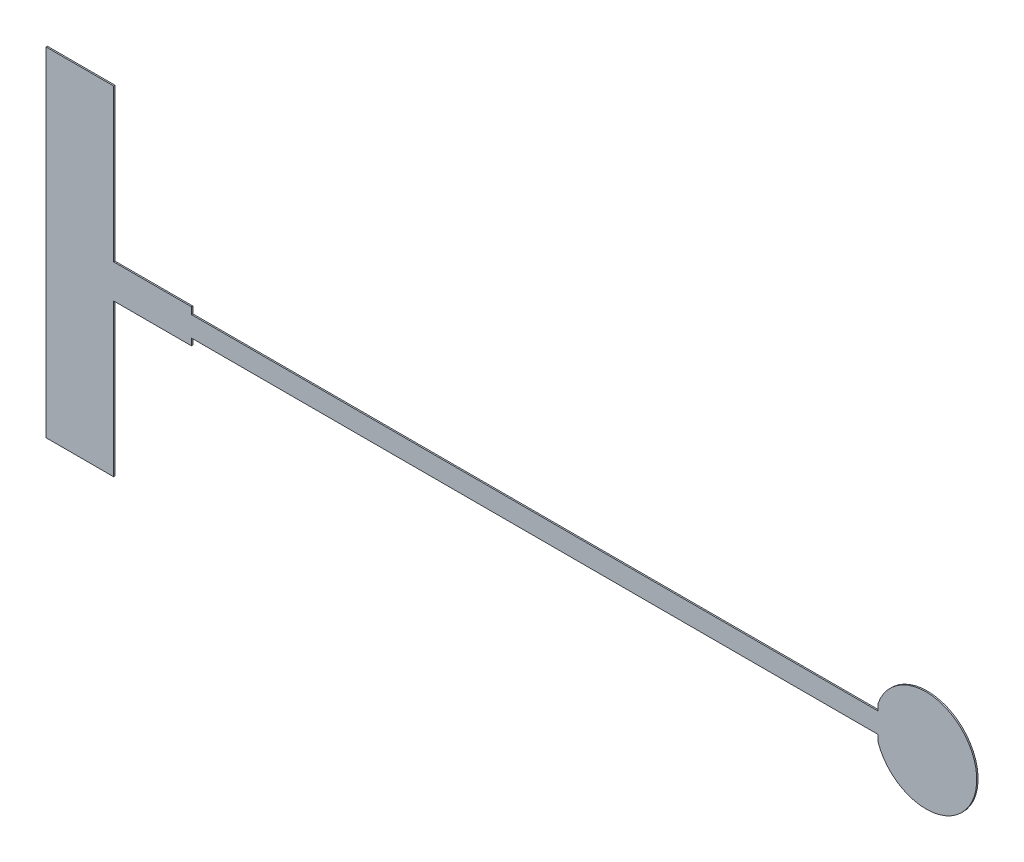
SolidWorks part; units mm, degrees
ref_plane "Front Plane" through (0, 0, 0) normal (0, 0, 1) x (1, 0, 0)
ref_plane "Top Plane" through (0, 0, 0) normal (0, 1, 0) x (1, 0, 0)
ref_plane "Right Plane" through (0, 0, 0) normal (1, 0, 0) x (0, 0, -1)
sketch "Sketch1" plane through (0, 0, 0) normal (0, 0, 1) x (1, 0, 0)
  line L0 (1000, 250) -> (5000, 250)
  line L1 (-1000, 2500) -> (1000, 2500)
  line L2 (-1000, 2500) -> (-1000, -2500)
  line L3 (-1000, -2500) -> (1000, -2500)
  line L4 (1000, 2500) -> (1000, 250)
  line L5 (-1000, 2500) -> (1000, -2500) construction
  line L6 (-1000, -2500) -> (1000, 2500) construction
  line L9 (1000, -250) -> (5000, -250)
  line L10 (5000, 250) -> (5000, 125)
  line L11 (-3000, 250) -> (5000, -250) construction
  line L12 (-3000, -250) -> (5000, 250) construction
  line L13 (5000, 125) -> (9000, 125)
  line L15 (5000, -125) -> (9000, -125)
  line L16 (9000, 125) -> (9000, 100)
  line L17 (1000, 125) -> (9000, -125) construction
  line L18 (1000, -125) -> (9000, 125) construction
  line L19 (9000, 100) -> (11256.6966, 100)
  line L21 (9000, -100) -> (11256.6966, -100)
  line L23 (6000, 100) -> (12000, -100) construction
  line L24 (6000, -100) -> (12000, 100) construction
  line L25 (1000, -250) -> (1000, -2500)
  line L26 (5000, -125) -> (5000, -250)
  line L27 (9000, -100) -> (9000, -125)
  arc A0 (11256.6966, -100) -> (11256.6966, 100) centre (12000, 0) ccw
  point P0 (0, 0)
  point P6 (1000, 0)
  point P11 (5000, 0)
  point P16 (9000, 0)
  dimension "D9" = 1500
  dimension "D1" = 2000
  dimension "D2" = 5000
  dimension "D3" = 500
  dimension "D4" = 4000
  dimension "D5" = 250
  dimension "D6" = 4000
  dimension "D7" = 200
extrude "Boss-Extrude1" add sketch "Sketch1" against normal blind 20
sketch "Sketch2" plane through (0, 0, 0) normal (0, 0, 1) x (1, 0, 0)
  line L0 (0, -11) -> (0, 11) construction
  line L1 (1000, 2500) -> (0, 2500)
  line L2 (1000, 2500) -> (1000, 250)
  line L3 (1000, 250) -> (0, 250)
  line L4 (0, 2500) -> (0, 250)
  line L5 (1000, -2500) -> (0, -2500)
  line L6 (1000, -2500) -> (1000, -250)
  line L7 (1000, -250) -> (0, -250)
  line L8 (0, -2500) -> (0, -250)
  dimension "D1" = 1000
  dimension "D2" = 2250
extrude "Cut-Extrude1" cut sketch "Sketch2" against normal through all
sketch "Sketch3" plane through (0, 0, 0) normal (0, 0, 1) x (1, 0, 0)
  line L0 (0, 0) -> (1098.3807, 0) construction
  line L1 (11, 0) -> (-11, 0) construction
  line L2 (5000, 250) -> (0, 250) construction
  line L3 (1500, 250) -> (3250, 250)
  line L4 (1500, 250) -> (1500, 200)
  line L5 (1500, 200) -> (3250, 200)
  line L7 (0, -250) -> (5000, -250) construction
  line L8 (1500, -250) -> (3250, -250)
  line L9 (1500, -250) -> (1500, -200)
  line L10 (1500, -200) -> (3250, -200)
  line L12 (0, -11) -> (0, 11) construction
  line L13 (3250, 200) -> (3250, 150)
  line L14 (3250, 250) -> (5000, 250)
  line L16 (3250, 150) -> (5000, 150)
  line L17 (5000, 250) -> (5000, 150)
  line L18 (3250, -250) -> (5000, -250)
  line L19 (3250, -200) -> (3250, -150)
  line L20 (3250, -150) -> (5000, -150)
  line L21 (5000, -250) -> (5000, -150)
  point P17 (1500, 225)
  dimension "D1" = 1098.3807
  dimension "D2" = 1750
  dimension "D3" = 50
  dimension "D4" = 1750
  dimension "D5" = 50
  dimension "D6" = 1500
  dimension "D7" = 1500
  dimension "D8" = 100
  dimension "D9" = 100
  dimension "D10" = 1750
  dimension "D11" = 1750
extrude "Cut-Extrude4" cut sketch "Sketch3" against normal through all contours L8 L18 L21 L20 L19 L10 L9
mirror "Mirror1" about plane through (0, 0, 0) normal (0, 1, 0) of "Cut-Extrude4"
sketch "Sketch5" plane through (0, 0, 0) normal (0, 0, 1) x (1, 0, 0)
  line L0 (0, -11) -> (0, 11) construction
  line L1 (0, -250) -> (11500, -250)
  line L2 (0, -250) -> (0, 250)
  line L3 (0, 250) -> (11500, 250)
  line L4 (11500, -250) -> (11500, 250)
  line L5 (0, -250) -> (1500, -250) construction
  dimension "D1" = 500
  dimension "D2" = 11500
extrude "Boss-Extrude2" add sketch "Sketch5" against normal blind 20
sketch "Sketch7" plane through (0, 0, 0) normal (0, 0, 1) x (1, 0, 0)
  line L0 (11292.8932, 250) -> (0, 250) construction
  line L1 (1150, 250) -> (11292.8932, 250)
  line L2 (1150, 250) -> (1150, 150)
  line L3 (1150, 150) -> (11292.8932, 150)
  line L4 (11292.8932, 250) -> (11292.8932, 150)
  line L5 (0, 2500) -> (0, 250) construction
  dimension "D1" = 1150
  dimension "D2" = 0
  dimension "D3" = 100
extrude "Cut-Extrude5" cut sketch "Sketch7" against normal through all
mirror "Mirror2" about plane through (0, 0, 0) normal (0, 1, 0) of "Cut-Extrude5"
